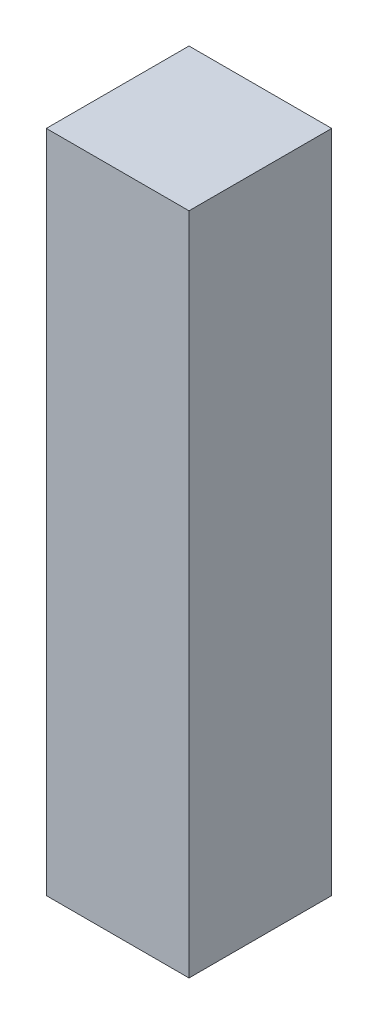
SolidWorks part; units mm, degrees
ref_plane "Front Plane" through (0, 0, 0) normal (0, 0, 1) x (1, 0, 0)
ref_plane "Top Plane" through (0, 0, 0) normal (0, 1, 0) x (1, 0, 0)
ref_plane "Right Plane" through (0, 0, 0) normal (1, 0, 0) x (0, 0, -1)
sketch "Sketch1" plane through (0, 0, 0) normal (0, 1, 0) x (1, 0, 0)
  line L1 (-127.5, -127.5) -> (127.5, -127.5)
  line L2 (-127.5, -127.5) -> (-127.5, 127.5)
  line L3 (-127.5, 127.5) -> (127.5, 127.5)
  line L4 (127.5, -127.5) -> (127.5, 127.5)
  line L5 (-127.5, -127.5) -> (127.5, 127.5) construction
  line L6 (-127.5, 127.5) -> (127.5, -127.5) construction
  point P0 (0, 0)
  dimension "D1" = 255
  dimension "D2" = 255
extrude "Boss-Extrude1" add sketch "Sketch1" along normal blind 1187.25
